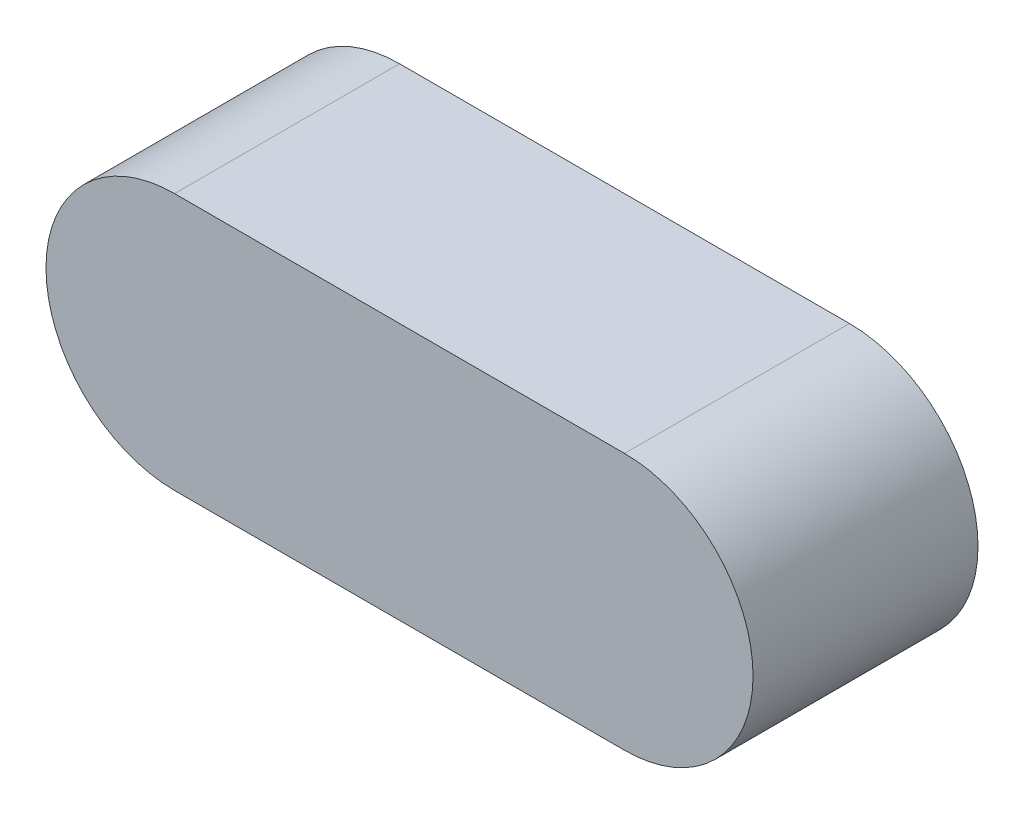
SolidWorks part; units mm, degrees
ref_plane "Piano frontale" through (0, 0, 0) normal (0, 0, 1) x (1, 0, 0)
ref_plane "Piano superiore" through (0, 0, 0) normal (0, 1, 0) x (1, 0, 0)
ref_plane "Piano destro" through (0, 0, 0) normal (1, 0, 0) x (0, 0, -1)
sketch "Schizzo1" plane through (0, 0, 0) normal (0, 0, 1) x (1, 0, 0)
  line L0 (0, 0) -> (14, 0) construction
  line L1 (0, 4) -> (14, 4)
  line L2 (0, -4) -> (14, -4)
  arc A0 (0, 4) -> (0, -4) centre (0, 0) ccw
  arc A1 (14, -4) -> (14, 4) centre (14, 0) ccw
  point P3 (7, 0)
  dimension "D1" = 14
  dimension "D2" = 8
extrude "Estrusione-Estrusione1" add sketch "Schizzo1" along normal blind 7
